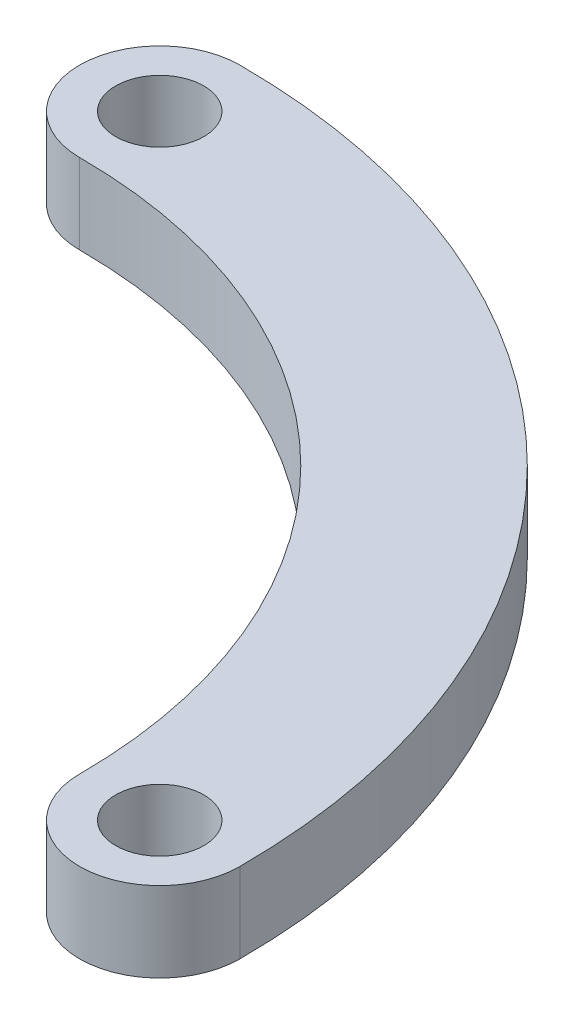
SolidWorks part; units mm, degrees
ref_plane "前视基准面" through (0, 0, 0) normal (0, 0, 1) x (1, 0, 0)
ref_plane "上视基准面" through (0, 0, 0) normal (0, 1, 0) x (1, 0, 0)
ref_plane "右视基准面" through (0, 0, 0) normal (1, 0, 0) x (0, 0, -1)
sketch "草图1" plane through (0, 0, 0) normal (0, 1, 0) x (1, 0, 0)
  arc A0 (20, 0) -> (0, 20) centre (0, 0) ccw
  arc A1 (26, 0) -> (0, 26) centre (0, 0) ccw
  arc A2 (0, 26) -> (0, 20) centre (0, 23) ccw
  arc A4 (20, 0) -> (26, 0) centre (23, 0) ccw
  circle A5 centre (0, 23) radius 1.65
  circle A6 centre (23, 0) radius 1.65
extrude "凸台-拉伸2" add sketch "草图1" along normal blind 3
